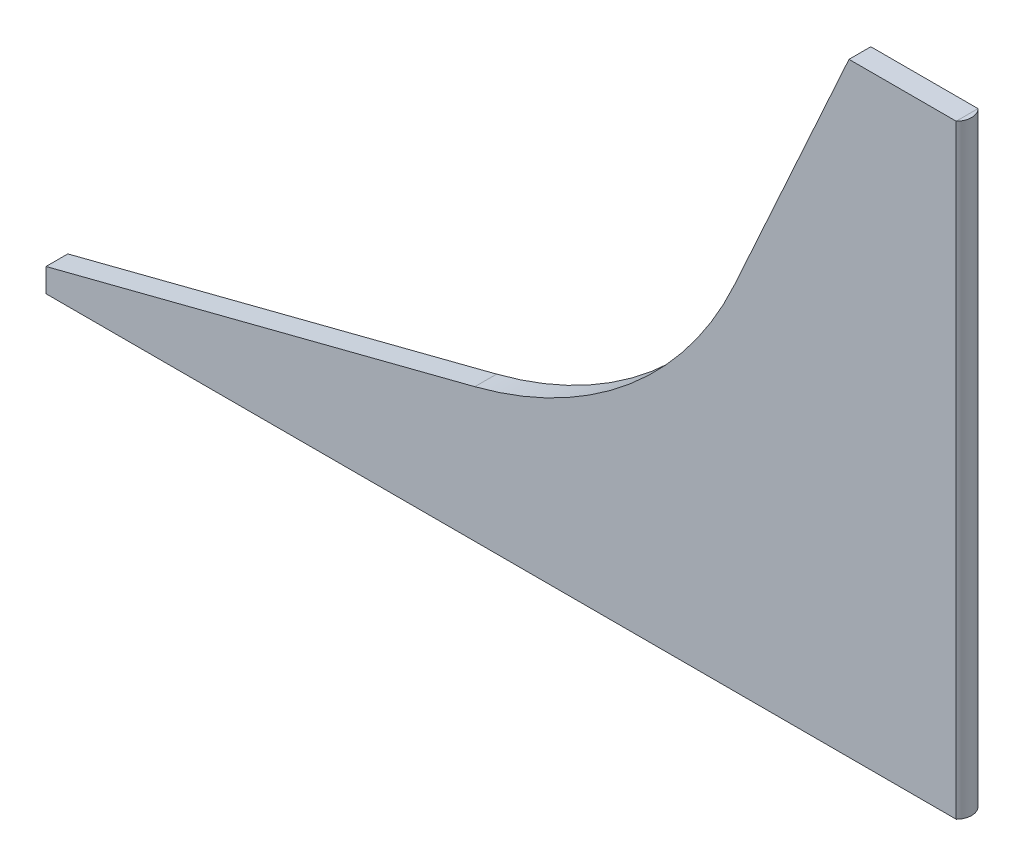
SolidWorks part; units mm, degrees
ref_plane "Front Plane" through (0, 0, 0) normal (0, 0, 1) x (1, 0, 0)
ref_plane "Top Plane" through (0, 0, 0) normal (0, 1, 0) x (1, 0, 0)
ref_plane "Right Plane" through (0, 0, 0) normal (1, 0, 0) x (0, 0, -1)
sketch "Sketch1" plane through (0, 0, 0) normal (0, 0, 1) x (1, 0, 0)
  line L0 (-236.7294, 0) -> (236.7294, 0) construction
  line L1 (-236.7294, 0) -> (0, 0)
  line L2 (0, 0) -> (389.5853, 0)
  line L3 (389.5853, 0) -> (389.5853, 416)
  line L4 (389.5853, 416) -> (315.8328, 416)
  line L5 (315.8328, 416) -> (236.9831, 242.1445)
  line L6 (58.3523, 92.1777) -> (-236.7294, 16.2749)
  line L7 (-236.7294, 16.2749) -> (-236.7294, 0)
  arc A0 (236.9831, 242.1445) -> (58.3523, 92.1777) centre (-8.9093, 353.6655) cw
  point P0 (389.5821, -0.9541)
  point P4 (0, 0)
  point P39 (183.5766, 124.3887)
  dimension "D4" = 270
  dimension "D1" = 90
  dimension "D3" = 416
extrude "Boss-Extrude1" add sketch "Sketch1" along normal blind 15
scale "Scale1" scale about centroid uniform scaling yes scale factor 0.6
ref_plane "Plane1" through (0, 184.5, 0) normal (0, 1, 0) x (1, 0, 0)
sketch "Sketch3" plane through (0, 184.5, 0) normal (0, 1, 0) x (1, 0, 0)
  line L0 (320.6939, -3) -> (320.6939, -12)
  arc A0 (320.6939, -3) -> (320.6939, -12) centre (316.1939, -7.5) cw
extrude "Boss-Extrude3" add sketch "Sketch3" along normal through all and the other way through all separate body
